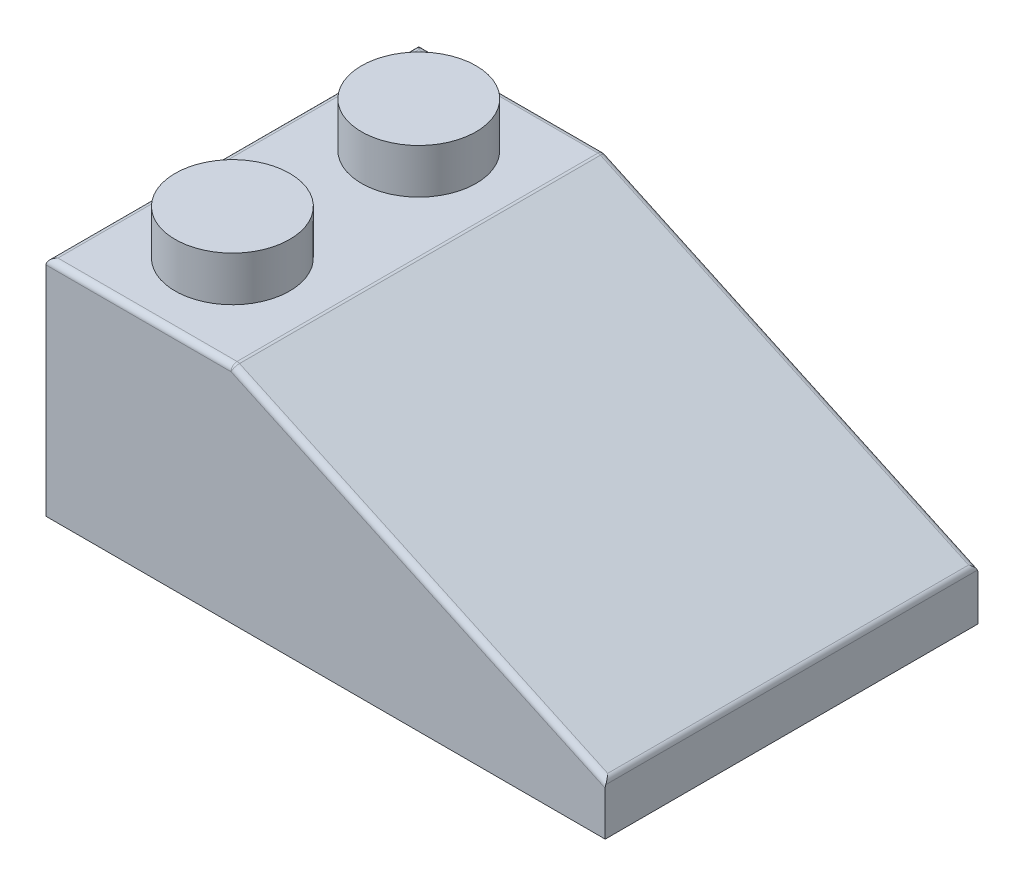
SolidWorks part; units mm, degrees
material "PW40:30:C1:0:1:2:Sc:3:Re:17:"
ref_plane "Front" through (0, 0, 0) normal (0, 0, 1) x (1, 0, 0)
ref_plane "Top" through (0, 0, 0) normal (0, 1, 0) x (1, 0, 0)
ref_plane "Right" through (0, 0, 0) normal (1, 0, 0) x (0, 0, -1)
sketch "Sketch1" plane through (0, 0, 0) normal (0, 1, 0) x (1, 0, 0)
  line L0 (0, 0) -> (0, 50.4571) construction
  line L1 (0, 0) -> (55.8847, 0) construction
  line L2 (-11.9062, 7.9375) -> (11.9062, 7.9375)
  line L3 (-11.9062, 7.9375) -> (-11.9062, -7.9375)
  line L4 (11.9062, -7.9375) -> (-11.9062, -7.9375)
  line L5 (11.9062, -7.9375) -> (11.9062, 7.9375)
  dimension "Length" = 23.8125
  dimension "Width" = 15.875
extrude "Base-Extrude" add sketch "Sketch1" along normal blind 9.525
sketch "Sketch2" plane through (0, 9.525, 0) normal (0, 1, 0) x (-1, 0, 0)
  line L0 (11.9062, -7.9375) -> (11.9062, 7.9375) construction
  line L1 (-11.9062, 7.9375) -> (11.9062, 7.9375) construction
  circle A0 centre (7.9375, 3.9688) radius 2.4384
  dimension "DotDiam" = 4.8768
  dimension "DotLSpc" = 3.9688
  dimension "DotWSpc" = 3.9688
extrude "Boss-Extrude1" add sketch "Sketch2" along normal blind 1.905
pattern_linear "LPattern4" count 3 spacing 7.9375 along (1, 0, 0) count 2 spacing 7.9375 along (0, 0, -1) of "Boss-Extrude1"
sketch "Sketch4" plane through (0, 0, 7.9375) normal (0, 0, 1) x (1, 0, 0)
  line L0 (-3.9688, 9.525) -> (11.9062, 2.159)
  line L1 (11.9062, 9.525) -> (-11.9062, 9.525) construction
  line L2 (11.9062, 9.525) -> (11.9062, 0) construction
  line L3 (11.9062, 0) -> (-11.9062, 0) construction
  line L4 (-11.9062, 9.525) -> (-11.9062, 0) construction
  line L5 (-3.9688, 9.525) -> (-3.9688, 11.43)
  line L6 (2.4384, 11.43) -> (-2.4384, 11.43) construction
  line L7 (11.9062, 2.159) -> (11.9063, 11.43)
  line L8 (11.9063, 11.43) -> (-3.9688, 11.43)
  dimension "D1" = 2.159
  dimension "D2" = 7.9375
extrude "Cut-Extrude1" cut sketch "Sketch4" against normal through all
shell "Shell1" thickness 1.5875
sketch "Sketch3" plane through (0, 0, 0) normal (0, -1, 0) x (1, 0, 0)
  line L0 (-11.9062, -7.9375) -> (-11.9062, 7.9375) construction
  circle A0 centre (-3.9688, 0) radius 2.4384
  dimension "InsDotDiam" = 4.8768
  dimension "InsDotSpc" = 7.9375
extrude "InsDot" add sketch "Sketch3" against normal up to next thin
pattern_linear "LPattern5" count 2 spacing 7.9375 along (1, 0, 0) of "InsDot"
fillet "Fillet1" radius 0.254 7 edges at (-7.9375, 9.525, -7.9375) (-7.9375, 9.525, 7.9375) (3.9688, 5.842, 7.9375) (-3.9688, 9.525, 0) (3.9688, 5.842, -7.9375) (11.9062, 2.159, 0) (-11.9062, 9.525, 0)
equation "\"InsDotPat@LPattern5\" = \"InsDotSpc@Sketch3\""
equation "\"WdotSpc@LPattern4\" = \"LdotSpc@LPattern4\""
equation "\"InsDots@LPattern5\" = \"Ldot@LPattern4\"-1"
